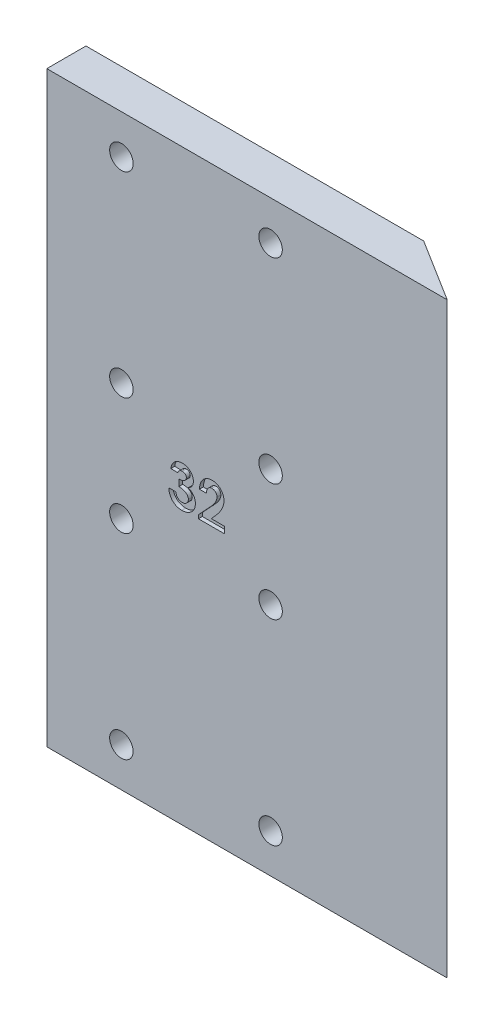
SolidWorks part; units mm, degrees
ref_plane "Front Plane" through (0, 0, 0) normal (0, 0, 1) x (1, 0, 0)
ref_plane "Top Plane" through (0, 0, 0) normal (0, 1, 0) x (1, 0, 0)
ref_plane "Right Plane" through (0, 0, 0) normal (1, 0, 0) x (0, 0, -1)
sketch "Sketch1" plane through (0, 0, 0) normal (0, 0, 1) x (1, 0, 0)
  line L0 (-38.1, -355.6) -> (-38.1, 355.6) construction
  line L1 (38.1, -355.6) -> (38.1, 355.6) construction
  line L2 (-38.1, -75) -> (-38.1, 75)
  line L3 (38.1, -75) -> (38.1, 75)
  line L6 (0, -75) -> (38.1, -75)
  line L7 (0, -75) -> (-38.1, -75)
  line L8 (0, 75) -> (-38.1, 75)
  line L9 (0, 75) -> (38.1, 75)
  circle A0 centre (-19.05, 65) radius 3
  circle A1 centre (-19.05, 15) radius 3
  circle A2 centre (19.05, 15) radius 3
  circle A3 centre (19.05, 65) radius 3
  circle A4 centre (19.05, -65) radius 3
  circle A5 centre (19.05, -15) radius 3
  circle A6 centre (-19.05, -15) radius 3
  circle A7 centre (-19.05, -65) radius 3
extrude "Boss-Extrude1" add sketch "Sketch1" along normal blind 10
sketch "Sketch2" plane through (0, -75, 0) normal (0, -1, 0) x (1, 0, 0)
  line L0 (38.1, -6.295) -> (373.0441, 203.2) construction
  line L1 (48.1645, 0) -> (64.1527, 10)
  line L6 (38.1, 10) -> (38.1, 0) construction
  line L7 (38.1, 10) -> (38.1, 0)
  line L8 (38.1, 0) -> (48.1645, 0)
  line L9 (38.1, 10) -> (64.1527, 10)
extrude "Boss-Extrude2" add sketch "Sketch2" against normal up to surface (150 mm away) up to face at (0, 75, 5)
sketch "Sketch3" plane through (0, 0, 10) normal (0, 0, 1) x (1, 0, 0)
  text T0 "<b>32</b>" font "Century Gothic" height 10
extrude "Cut-Extrude1" cut sketch "Sketch3" against normal blind 1
